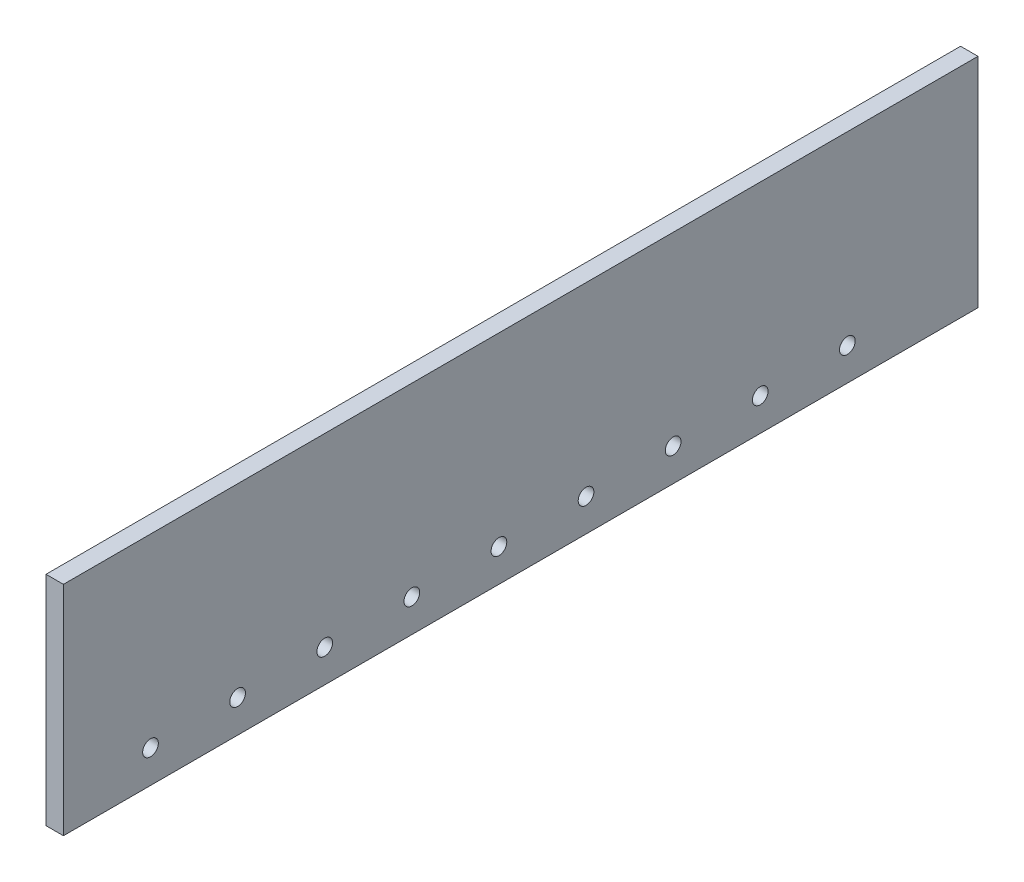
SolidWorks part; units mm, degrees
ref_plane "Front Plane" through (0, 0, 0) normal (0, 0, 1) x (1, 0, 0)
ref_plane "Top Plane" through (0, 0, 0) normal (0, 1, 0) x (1, 0, 0)
ref_plane "Right Plane" through (0, 0, 0) normal (1, 0, 0) x (0, 0, -1)
sketch "Sketch2" plane through (0, 0, 0) normal (1, 0, 0) x (0, 0, -1)
  line L0 (-84.2593, 50.216) -> (125.7407, 50.216)
  line L1 (-84.2593, 50.216) -> (-84.2593, 0.216)
  line L2 (125.7407, 50.216) -> (125.7407, 0.216)
  line L3 (-84.2593, 0.216) -> (125.7407, 0.216)
  circle A0 centre (-64.2593, 7.716) radius 1.8
  circle A1 centre (-44.2593, 7.716) radius 1.8
  circle A2 centre (-24.2593, 7.716) radius 1.8
  circle A3 centre (-4.2593, 7.716) radius 1.8
  circle A4 centre (15.7407, 7.716) radius 1.8
  circle A5 centre (35.7407, 7.716) radius 1.8
  circle A6 centre (55.7407, 7.716) radius 1.8
  circle A7 centre (75.7407, 7.716) radius 1.8
  circle A8 centre (95.7407, 7.716) radius 1.8
  dimension "D3" = 7.5
  dimension "D1" = 50
  dimension "D2" = 210
  dimension "D4" = 20
  dimension "D5" = 9
extrude "Boss-Extrude1" add sketch "Sketch2" along normal blind 4
